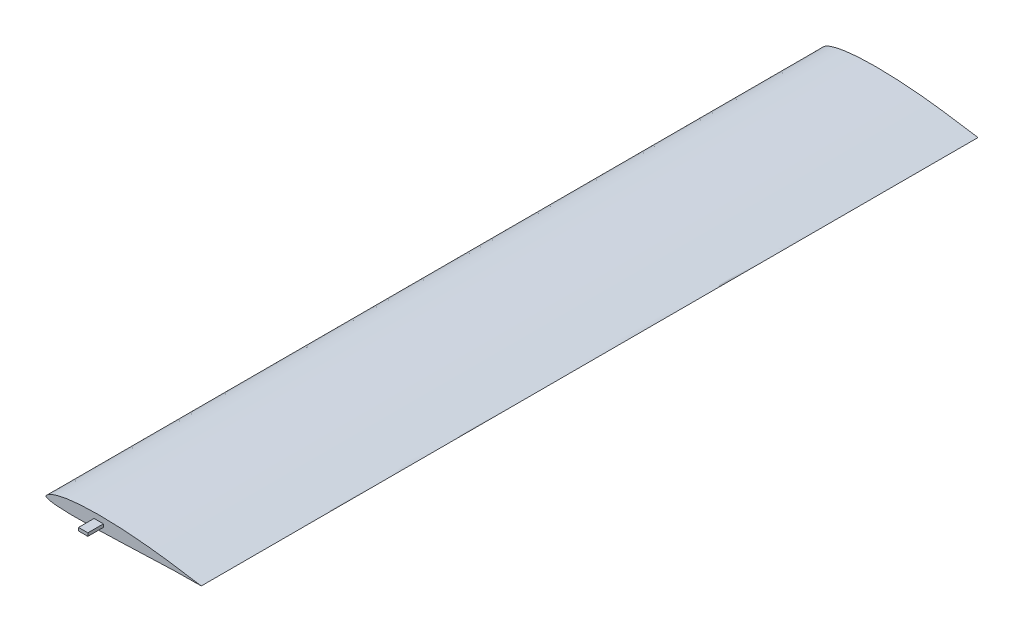
SolidWorks part; units mm, degrees
ref_plane "Front Plane" through (0, 0, 0) normal (0, 0, 1) x (1, 0, 0)
ref_plane "Top Plane" through (0, 0, 0) normal (0, 1, 0) x (1, 0, 0)
ref_plane "Right Plane" through (0, 0, 0) normal (1, 0, 0) x (0, 0, -1)
curve "Curve1"
  spline degree 3 poles (49.6515, 0.009, 0) (50.0884, -0.0053, 0) (49.6522, 0.033, 0) (49.3011, 0.0832, 0) (48.4593, 0.1945, 0) (47.4415, 0.3499, 0) (46.1338, 0.5549, 0) (44.6155, 0.7993, 0) (42.8923, 1.0751, 0) (40.9958, 1.371, 0) (38.9477, 1.6747, 0) (36.7703, 1.9711, 0) (34.4838, 2.2498, 0) (32.109, 2.5048, 0) (29.6686, 2.7322, 0) (27.1889, 2.9318, 0) (24.6971, 3.0996, 0) (22.2188, 3.2252, 0) (19.7784, 3.3048, 0) (17.3996, 3.3388, 0) (15.1043, 3.321, 0) (12.9138, 3.2492, 0) (10.8475, 3.1296, 0) (8.9245, 2.9596, 0) (7.1613, 2.7404, 0) (5.5715, 2.4767, 0) (4.1671, 2.1739, 0) (2.9576, 1.8376, 0) (1.9505, 1.4773, 0) (1.1488, 1.103, 0) (0.5587, 0.7311, 0) (0.2281, 0.4366, 0) (0.09, 0.2394, 0) (0.0408, 0.1522, 0) (0.0104, 0.0738, 0) (-0.0015, 0.012, 0) (0.0009, -0.0367, 0) (0.0247, -0.0804, 0) (0.0694, -0.1305, 0) (0.1411, -0.1885, 0) (0.3144, -0.2962, 0) (0.7005, -0.4536, 0) (1.3781, -0.6282, 0) (2.3375, -0.7877, 0) (3.539, -0.9182, 0) (4.9742, -1.0154, 0) (6.6312, -1.0793, 0) (8.4956, -1.1107, 0) (10.5497, -1.112, 0) (12.7728, -1.0868, 0) (15.1414, -1.0389, 0) (17.6298, -0.9723, 0) (20.2103, -0.8906, 0) (22.8538, -0.7976, 0) (25.5303, -0.6969, 0) (28.2091, -0.5925, 0) (30.859, -0.4876, 0) (33.449, -0.3866, 0) (35.9478, -0.2924, 0) (38.325, -0.208, 0) (40.551, -0.1358, 0) (42.5964, -0.0785, 0) (44.4361, -0.0365, 0) (46.0378, -0.0091, 0) (47.399, 0.0043, 0) (48.4441, 0.0096, 0) (49.2972, 0.0042, 0) (49.6515, 0.009, 0) (50.0884, -0.0053, 0) (49.6522, 0.033, 0) knots -0.014204 -0.006419 -0.001632 0 0.001631 0.006435 0.014221 0.024766 0.037827 0.053149 0.070474 0.089536 0.110075 0.13186 0.154693 0.178371 0.20268 0.227364 0.252133 0.276728 0.300939 0.324527 0.347267 0.368992 0.389507 0.408628 0.426224 0.442179 0.456396 0.468805 0.479372 0.488086 0.494968 0.500034 0.501036 0.502094 0.502997 0.503513 0.503956 0.504409 0.504955 0.505943 0.50713 0.510998 0.518232 0.527846 0.539809 0.554056 0.57049 0.588974 0.609342 0.631393 0.654894 0.67959 0.705203 0.731447 0.75802 0.78462 0.810936 0.836657 0.861473 0.885081 0.907188 0.927507 0.945765 0.961712 0.975122 0.985796 0.993581 0.998368 1 1.001631 1.006435 1.014221 periodic
sketch "Sketch1" plane through (0, 0, 0) normal (0, 0, 1) x (1, 0, 0)
  spline S0 degree 3 poles (49.6515, 0.009) (50.0884, -0.0053) (49.6522, 0.033) (49.3011, 0.0832) (48.4593, 0.1945) (47.4415, 0.3499) (46.1338, 0.5549) (44.6155, 0.7993) (42.8923, 1.0751) (40.9958, 1.371) (38.9477, 1.6747) (36.7703, 1.9711) (34.4838, 2.2498) (32.109, 2.5048) (29.6686, 2.7322) (27.1889, 2.9318) (24.6971, 3.0996) (22.2188, 3.2252) (19.7784, 3.3048) (17.3996, 3.3388) (15.1043, 3.321) (12.9138, 3.2492) (10.8475, 3.1296) (8.9245, 2.9596) (7.1613, 2.7404) (5.5715, 2.4767) (4.1671, 2.1739) (2.9576, 1.8376) (1.9505, 1.4773) (1.1488, 1.103) (0.5587, 0.7311) (0.2281, 0.4366) (0.09, 0.2394) (0.0408, 0.1522) (0.0104, 0.0738) (-0.0015, 0.012) (0.0009, -0.0367) (0.0247, -0.0804) (0.0694, -0.1305) (0.1411, -0.1885) (0.3144, -0.2962) (0.7005, -0.4536) (1.3781, -0.6282) (2.3375, -0.7877) (3.539, -0.9182) (4.9742, -1.0154) (6.6312, -1.0793) (8.4956, -1.1107) (10.5497, -1.112) (12.7728, -1.0868) (15.1414, -1.0389) (17.6298, -0.9723) (20.2103, -0.8906) (22.8538, -0.7976) (25.5303, -0.6969) (28.2091, -0.5925) (30.859, -0.4876) (33.449, -0.3866) (35.9478, -0.2924) (38.325, -0.208) (40.551, -0.1358) (42.5964, -0.0785) (44.4361, -0.0365) (46.0378, -0.0091) (47.399, 0.0043) (48.4441, 0.0096) (49.2972, 0.0042) (49.6515, 0.009) (50.0884, -0.0053) (49.6522, 0.033) knots -0.014204 -0.006419 -0.001632 0 0.001631 0.006435 0.014221 0.024766 0.037827 0.053149 0.070474 0.089536 0.110075 0.13186 0.154693 0.178371 0.20268 0.227364 0.252133 0.276728 0.300939 0.324527 0.347267 0.368992 0.389507 0.408628 0.426224 0.442179 0.456396 0.468805 0.479372 0.488086 0.494968 0.500034 0.501036 0.502094 0.502997 0.503513 0.503956 0.504409 0.504955 0.505943 0.50713 0.510998 0.518232 0.527846 0.539809 0.554056 0.57049 0.588974 0.609342 0.631393 0.654894 0.67959 0.705203 0.731447 0.75802 0.78462 0.810936 0.836657 0.861473 0.885081 0.907188 0.927507 0.945765 0.961712 0.975122 0.985796 0.993581 0.998368 1 1.001631 1.006435 1.014221 only from (50, 0) to (50, 0) construction
  spline S1 degree 3 poles (49.6515, 0.009) (50.0884, -0.0053) (49.6522, 0.033) (49.3011, 0.0832) (48.4593, 0.1945) (47.4415, 0.3499) (46.1338, 0.5549) (44.6155, 0.7993) (42.8923, 1.0751) (40.9958, 1.371) (38.9477, 1.6747) (36.7703, 1.9711) (34.4838, 2.2498) (32.109, 2.5048) (29.6686, 2.7322) (27.1889, 2.9318) (24.6971, 3.0996) (22.2188, 3.2252) (19.7784, 3.3048) (17.3996, 3.3388) (15.1043, 3.321) (12.9138, 3.2492) (10.8475, 3.1296) (8.9245, 2.9596) (7.1613, 2.7404) (5.5715, 2.4767) (4.1671, 2.1739) (2.9576, 1.8376) (1.9505, 1.4773) (1.1488, 1.103) (0.5587, 0.7311) (0.2281, 0.4366) (0.09, 0.2394) (0.0408, 0.1522) (0.0104, 0.0738) (-0.0015, 0.012) (0.0009, -0.0367) (0.0247, -0.0804) (0.0694, -0.1305) (0.1411, -0.1885) (0.3144, -0.2962) (0.7005, -0.4536) (1.3781, -0.6282) (2.3375, -0.7877) (3.539, -0.9182) (4.9742, -1.0154) (6.6312, -1.0793) (8.4956, -1.1107) (10.5497, -1.112) (12.7728, -1.0868) (15.1414, -1.0389) (17.6298, -0.9723) (20.2103, -0.8906) (22.8538, -0.7976) (25.5303, -0.6969) (28.2091, -0.5925) (30.859, -0.4876) (33.449, -0.3866) (35.9478, -0.2924) (38.325, -0.208) (40.551, -0.1358) (42.5964, -0.0785) (44.4361, -0.0365) (46.0378, -0.0091) (47.399, 0.0043) (48.4441, 0.0096) (49.2972, 0.0042) (49.6515, 0.009) (50.0884, -0.0053) (49.6522, 0.033) knots -0.014204 -0.006419 -0.001632 0 0.001631 0.006435 0.014221 0.024766 0.037827 0.053149 0.070474 0.089536 0.110075 0.13186 0.154693 0.178371 0.20268 0.227364 0.252133 0.276728 0.300939 0.324527 0.347267 0.368992 0.389507 0.408628 0.426224 0.442179 0.456396 0.468805 0.479372 0.488086 0.494968 0.500034 0.501036 0.502094 0.502997 0.503513 0.503956 0.504409 0.504955 0.505943 0.50713 0.510998 0.518232 0.527846 0.539809 0.554056 0.57049 0.588974 0.609342 0.631393 0.654894 0.67959 0.705203 0.731447 0.75802 0.78462 0.810936 0.836657 0.861473 0.885081 0.907188 0.927507 0.945765 0.961712 0.975122 0.985796 0.993581 0.998368 1 1.001631 1.006435 1.014221 only from (50, 0) to (50, 0)
extrude "Boss-Extrude1" add sketch "Sketch1" along normal blind 250
sketch "Sketch2" plane through (0, 0, 250) normal (0, 0, 1) x (1, 0, 0)
  line L0 (0, 0) -> (50, 0) construction
  line L1 (15.473, 1.5494) -> (18.473, 1.5494)
  line L2 (15.473, 1.5494) -> (15.473, 0.5494)
  line L3 (15.473, 0.5494) -> (18.473, 0.5494)
  line L4 (18.473, 1.5494) -> (18.473, 0.5494)
  spline S0 degree 3 poles (49.6515, 0.009) (50.0884, -0.0053) (49.6522, 0.033) (49.3011, 0.0832) (48.4593, 0.1945) (47.4415, 0.3499) (46.1338, 0.5549) (44.6155, 0.7993) (42.8923, 1.0751) (40.9958, 1.371) (38.9477, 1.6747) (36.7703, 1.9711) (34.4838, 2.2498) (32.109, 2.5048) (29.6686, 2.7322) (27.1889, 2.9318) (24.6971, 3.0996) (22.2188, 3.2252) (19.7784, 3.3048) (17.3996, 3.3388) (15.1043, 3.321) (12.9138, 3.2492) (10.8475, 3.1296) (8.9245, 2.9596) (7.1613, 2.7404) (5.5715, 2.4767) (4.1671, 2.1739) (2.9576, 1.8376) (1.9505, 1.4773) (1.1488, 1.103) (0.5587, 0.7311) (0.2281, 0.4366) (0.09, 0.2394) (0.0408, 0.1522) (0.0104, 0.0738) (-0.0015, 0.012) (0.0009, -0.0367) (0.0247, -0.0804) (0.0694, -0.1305) (0.1411, -0.1885) (0.3144, -0.2962) (0.7005, -0.4536) (1.3781, -0.6282) (2.3375, -0.7877) (3.539, -0.9182) (4.9742, -1.0154) (6.6312, -1.0793) (8.4956, -1.1107) (10.5497, -1.112) (12.7728, -1.0868) (15.1414, -1.0389) (17.6298, -0.9723) (20.2103, -0.8906) (22.8538, -0.7976) (25.5303, -0.6969) (28.2091, -0.5925) (30.859, -0.4876) (33.449, -0.3866) (35.9478, -0.2924) (38.325, -0.208) (40.551, -0.1358) (42.5964, -0.0785) (44.4361, -0.0365) (46.0378, -0.0091) (47.399, 0.0043) (48.4441, 0.0096) (49.2972, 0.0042) (49.6515, 0.009) (50.0884, -0.0053) (49.6522, 0.033) knots -0.014204 -0.006419 -0.001632 0 0.001631 0.006435 0.014221 0.024766 0.037827 0.053149 0.070474 0.089536 0.110075 0.13186 0.154693 0.178371 0.20268 0.227364 0.252133 0.276728 0.300939 0.324527 0.347267 0.368992 0.389507 0.408628 0.426224 0.442179 0.456396 0.468805 0.479372 0.488086 0.494968 0.500034 0.501036 0.502094 0.502997 0.503513 0.503956 0.504409 0.504955 0.505943 0.50713 0.510998 0.518232 0.527846 0.539809 0.554056 0.57049 0.588974 0.609342 0.631393 0.654894 0.67959 0.705203 0.731447 0.75802 0.78462 0.810936 0.836657 0.861473 0.885081 0.907188 0.927507 0.945765 0.961712 0.975122 0.985796 0.993581 0.998368 1 1.001631 1.006435 1.014221 only from (50, 0) to (50, 0) construction
  dimension "D1" = 3
  dimension "D2" = 1
  dimension "D3" = 1.5494
  dimension "D4" = 31.527
extrude "Boss-Extrude2" add sketch "Sketch2" along normal blind 5
